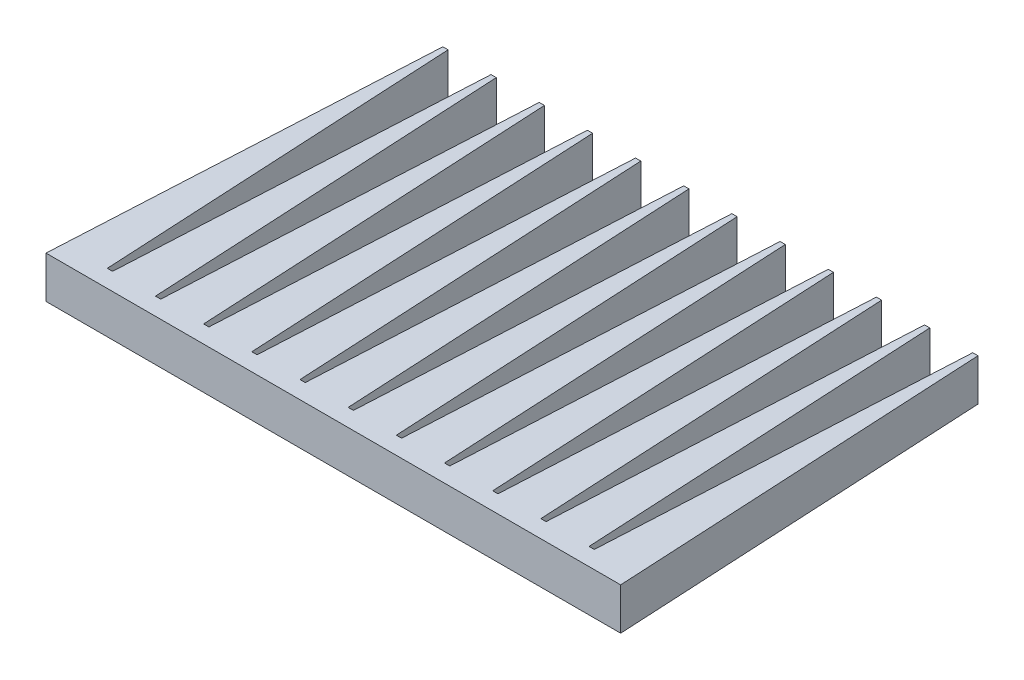
SolidWorks part; units mm, degrees
material "1060 Alloy"
ref_plane "Front Plane" through (0, 0, 0) normal (0, 0, 1) x (1, 0, 0)
ref_plane "Top Plane" through (0, 0, 0) normal (0, 1, 0) x (1, 0, 0)
ref_plane "Right Plane" through (0, 0, 0) normal (1, 0, 0) x (0, 0, -1)
sketch "Sketch1" plane through (0, 0, 0) normal (0, 1, 0) x (1, 0, 0)
  line L0 (0.0529, -1.2333) -> (58.0796, -1.2333)
  line L4 (58.078, 3.7667) -> (52.68, 106.7667)
  line L5 (52.68, 106.7667) -> (51.18, 106.7667)
  line L6 (51.18, 106.7667) -> (45.782, 3.7667)
  line L7 (45.782, 3.7667) -> (44.282, 3.7667)
  line L8 (44.282, 3.7667) -> (38.884, 106.7667)
  line L9 (37.384, 106.7667) -> (31.986, 3.7667)
  line L10 (31.986, 3.7667) -> (30.486, 3.7667)
  line L11 (38.884, 106.7667) -> (37.384, 106.7667)
  line L12 (30.486, 3.7667) -> (25.088, 106.7667)
  line L13 (23.588, 106.7667) -> (18.19, 3.7667)
  line L14 (18.19, 3.7667) -> (16.69, 3.7667)
  line L15 (25.088, 106.7667) -> (23.588, 106.7667)
  line L16 (16.69, 3.7667) -> (11.292, 106.7667)
  line L17 (9.792, 106.7667) -> (4.394, 3.7667)
  line L18 (4.394, 3.7667) -> (2.894, 3.7667)
  line L19 (11.292, 106.7667) -> (9.792, 106.7667)
  line L20 (2.894, 3.7667) -> (-2.504, 106.7667)
  line L21 (-4.004, 106.7667) -> (-9.402, 3.7667)
  line L22 (-9.402, 3.7667) -> (-10.902, 3.7667)
  line L23 (-2.504, 106.7667) -> (-4.004, 106.7667)
  line L24 (-10.902, 3.7667) -> (-16.3, 106.7667)
  line L25 (-17.8, 106.7667) -> (-23.198, 3.7667)
  line L26 (-23.198, 3.7667) -> (-24.698, 3.7667)
  line L27 (-16.3, 106.7667) -> (-17.8, 106.7667)
  line L28 (-24.698, 3.7667) -> (-30.096, 106.7667)
  line L29 (-31.596, 106.7667) -> (-36.994, 3.7667)
  line L30 (-36.994, 3.7667) -> (-38.494, 3.7667)
  line L31 (-30.096, 106.7667) -> (-31.596, 106.7667)
  line L32 (-38.494, 3.7667) -> (-43.892, 106.7667)
  line L33 (-45.392, 106.7667) -> (-50.79, 3.7667)
  line L34 (-50.79, 3.7667) -> (-52.29, 3.7667)
  line L35 (-43.892, 106.7667) -> (-45.392, 106.7667)
  line L36 (-52.29, 3.7667) -> (-57.688, 106.7667)
  line L37 (-59.188, 106.7667) -> (-64.586, 3.7667)
  line L38 (-64.586, 3.7667) -> (-66.086, 3.7667)
  line L39 (-57.688, 106.7667) -> (-59.188, 106.7667)
  line L40 (-66.086, 3.7667) -> (-71.484, 106.7667)
  line L41 (-72.984, 106.7667) -> (-78.382, 3.7667)
  line L42 (-78.382, 3.7667) -> (-79.882, 3.7667)
  line L43 (-71.484, 106.7667) -> (-72.984, 106.7667)
  line L44 (-79.882, 3.7667) -> (-85.28, 106.7667)
  line L45 (-86.78, 106.7667) -> (-92.178, 3.7667)
  line L46 (-92.178, 3.7667) -> (-93.678, 3.7667)
  line L47 (-85.28, 106.7667) -> (-86.78, 106.7667)
  line L48 (-93.678, 3.7667) -> (-99.076, 106.7667)
  line L49 (-100.576, 106.7667) -> (-105.974, 3.7667)
  line L50 (58.0796, -1.2333) -> (58.3401, -1.2333)
  line L51 (-99.076, 106.7667) -> (-100.576, 106.7667)
  line L54 (-105.974, 3.7667) -> (-107.474, 3.7667) [skipped]
  line L55 (58.078, 3.7667) -> (58.3401, -1.2333)
  line L56 (-105.974, 3.7667) -> (-106.236, -1.2333)
  line L57 (0.0529, -1.2333) -> (-106.236, -1.2333)
  dimension "D3" = 1.5
  dimension "D4" = 87
  dimension "D5" = 108
  dimension "D2" = 1.5
  dimension "D7" = 87
  dimension "D1" = 5
  dimension "D6" = 12
extrude "Boss-Extrude1" add sketch "Sketch1" along normal blind 12
equation "\"A\" = 108"
equation "\"B\" = 12"
equation "\"C\"= 1.5"
equation "\"D3@Sketch1\"=\"C\""
equation "\"D5@Sketch1\"=\"A\""
equation "\"D2@Sketch1\"=\"C\""
equation "\"D1@Boss-Extrude1\"=\"B\""
